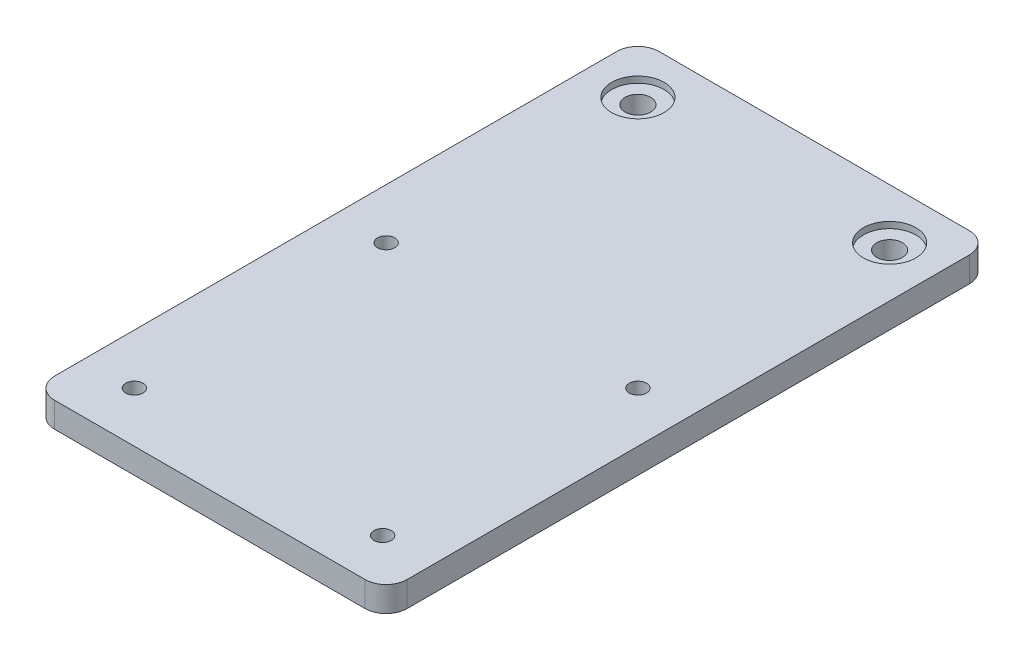
SolidWorks part; units mm, degrees
ref_plane "前视基准面" through (0, 0, 0) normal (0, 0, 1) x (1, 0, 0)
ref_plane "上视基准面" through (0, 0, 0) normal (0, 1, 0) x (1, 0, 0)
ref_plane "右视基准面" through (0, 0, 0) normal (1, 0, 0) x (0, 0, -1)
sketch "草图1" plane through (0, 0, 0) normal (0, 1, 0) x (1, 0, 0)
  line L1 (37, -72) -> (-37, -72)
  line L2 (42, -67) -> (42, 67)
  line L3 (37, 72) -> (-37, 72)
  line L4 (-42, -67) -> (-42, 67)
  line L5 (42, -72) -> (-42, 72) construction
  line L6 (42, 72) -> (-42, -72) construction
  arc A0 (-37, -72) -> (-42, -67) centre (-37, -67) cw
  arc A1 (37, -72) -> (42, -67) centre (37, -67) ccw
  arc A2 (42, 67) -> (37, 72) centre (37, 67) ccw
  arc A3 (-42, 67) -> (-37, 72) centre (-37, 67) cw
  point P0 (0, 0)
  dimension "D3" = 5
  dimension "D1" = 84
  dimension "D2" = 144
extrude "凸台-拉伸1" add sketch "草图1" along normal blind 6
sketch "草图2" plane through (0, 0, 0) normal (0, -1, 0) x (1, 0, 0)
  line L0 (-37, 72) -> (37, 72) construction
  line L1 (-42, -67) -> (-42, 67) construction
  line L2 (42, 67) -> (42, -67) construction
  line L3 (37, -72) -> (-37, -72) construction
  circle A0 centre (-30, 60) radius 2.05
  circle A1 centre (30, 60.8347) radius 2.05
  circle A2 centre (-30, 0) radius 2.05
  circle A3 centre (30, 0) radius 2.05
  circle A4 centre (-30, -60) radius 3.05
  circle A5 centre (30, -60) radius 3.05
  dimension "D3" = 4.1
  dimension "D4" = 4.1
  dimension "D8" = 4.1
  dimension "D9" = 4.1
  dimension "D14" = 12
  dimension "D18" = 6.1
  dimension "D19" = 6.1
  dimension "D2" = 12
  dimension "D5" = 72
  dimension "D6" = 72
  dimension "D7" = 12
  dimension "D10" = 11.1653
  dimension "D11" = 12
  dimension "D12" = 12
  dimension "D13" = 12
  dimension "D15" = 12
  dimension "D16" = 12
  dimension "D17" = 12
extrude "切除-拉伸1" cut sketch "草图2" against normal blind 6
sketch "草图3" plane through (0, 0, 0) normal (0, -1, 0) x (1, 0, 0)
  circle A0 centre (-30, 60) radius 5.25
  circle A1 centre (30, 60.8347) radius 5.25
  circle A2 centre (-30, 0) radius 5.25
  circle A3 centre (30, 0) radius 5.25
  dimension "D1" = 10.5
extrude "切除-拉伸2" cut sketch "草图3" against normal blind 1.3
sketch "草图5" plane through (0, 6, 0) normal (0, 1, 0) x (1, 0, 0)
  circle A2 centre (-30, 60) radius 6.25
  circle A3 centre (30, 60) radius 6.25
  dimension "D1" = 12.5
  dimension "D2" = 12.5
extrude "切除-拉伸3" cut sketch "草图5" against normal blind 1.5
